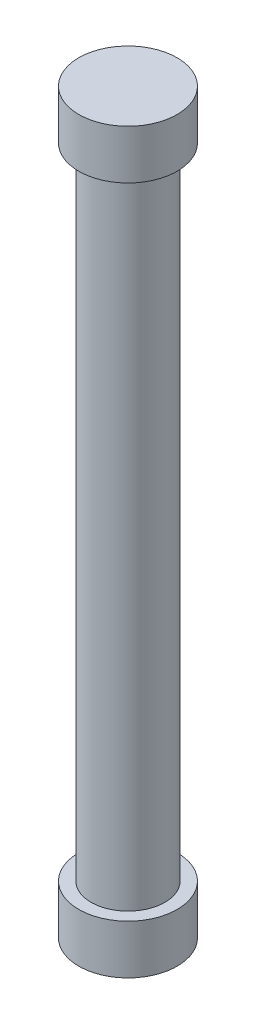
SolidWorks part; units mm, degrees
material "Alloy Steel (SS)"
ref_plane "Front Plane" through (0, 0, 0) normal (0, 0, 1) x (1, 0, 0)
ref_plane "Top Plane" through (0, 0, 0) normal (0, 1, 0) x (1, 0, 0)
ref_plane "Right Plane" through (0, 0, 0) normal (1, 0, 0) x (0, 0, -1)
sketch "Sketch1" plane through (0, 0, 0) normal (0, 0, 1) x (1, 0, 0)
  line L0 (0, 26.0252) -> (0, -3.9748)
  line L1 (0, -3.9748) -> (-2, -3.9748)
  line L2 (-2, -3.9748) -> (-2, -1.9748)
  line L3 (-2, -1.9748) -> (-1.5, -1.9748)
  line L4 (-1.5, -1.9748) -> (-1.5, 24.0252)
  line L5 (-1.5, 24.0252) -> (-2, 24.0252)
  line L6 (-2, 24.0252) -> (-2, 26.0252)
  line L7 (-2, 26.0252) -> (0, 26.0252)
  dimension "D1" = 1.5
  dimension "D2" = 2
  dimension "D3" = 2
  dimension "D4" = 2
  dimension "D5" = 2
  dimension "D6" = 30
revolve "Revolve1" add sketch "Sketch1" angle 360 about L0
